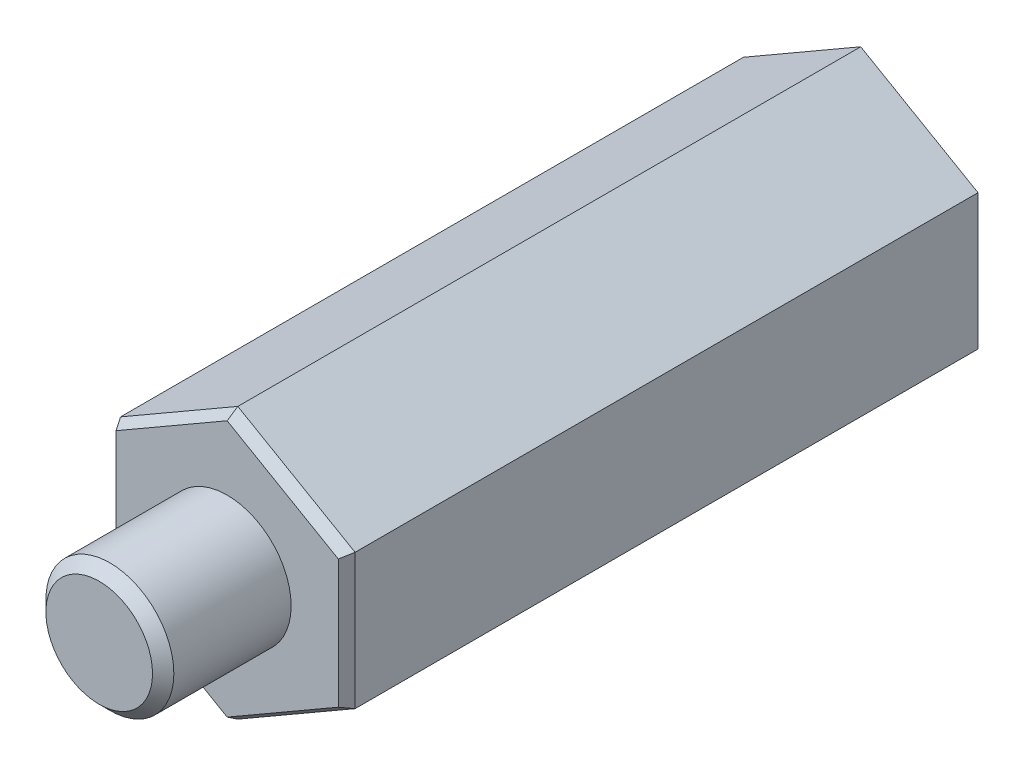
SolidWorks part; units mm, degrees
material "ｽﾃﾝﾚｽ鋼(鋳造)"
ref_plane "正面" through (0, 0, 0) normal (0, 0, 1) x (1, 0, 0)
ref_plane "平面" through (0, 0, 0) normal (0, 1, 0) x (1, 0, 0)
ref_plane "右側面" through (0, 0, 0) normal (1, 0, 0) x (0, 0, -1)
sketch "ｽｹｯﾁ1" plane through (0, 0, 0) normal (0, 0, 1) x (1, 0, 0)
  line L1 (-2.75, 1.5877) -> (-2.75, -1.5877)
  line L2 (-2.75, -1.5877) -> (0, -3.1754)
  line L3 (0, -3.1754) -> (2.75, -1.5877)
  line L4 (2.75, -1.5877) -> (2.75, 1.5877)
  line L5 (2.75, 1.5877) -> (0, 3.1754)
  line L6 (0, 3.1754) -> (-2.75, 1.5877)
  circle A0 centre (0, 0) radius 2.75 construction
  dimension "D1" = 5.5
extrude "ﾎﾞｽ - 押し出し1" add sketch "ｽｹｯﾁ1" against normal blind 15
hole_wizard "M3x0.5 ねじ穴1" positions "ｽｹｯﾁ2" profile "ｽｹｯﾁ3" tap size "M3x0.5" standard "JIS"
sketch "ｽｹｯﾁ2" plane through (0, 0, -15) normal (0, 0, -1) x (-1, 0, 0)
  point P0 (0, 0)
sketch "ｽｹｯﾁ3" plane through (0, 0, -15) normal (1, 0, 0) x (0, 1, 0)
  line L0 (0, 0) -> (0, 8.7511)
  line L1 (0, 8.7511) -> (1.25, 8)
  line L2 (1.25, 8) -> (1.25, 0.275)
  line L3 (1.25, 0.275) -> (1.525, 0)
  line L5 (1.525, 0) -> (0, 0)
  line L6 (-1.25, 0.275) -> (-1.525, 0) construction
  line L10 (0, 8.7511) -> (-1.25, 8) construction
  line L11 (0, -6.35) -> (0, 107.95) construction
  dimension "ねじ下穴ﾄﾞﾘﾙ直径" = 2.5
  dimension "ねじ下穴ﾄﾞﾘﾙの深さ" = 8
  dimension "表面の皿穴の直径" = 3.05
  dimension "表面の皿穴の角度" = 90
  dimension "ﾄﾞﾘﾙ角度" = 118
cosmetic thread "穴のねじ山1" parameters "D1"=6, "D2"=3
sketch "ｽｹｯﾁ4" plane through (0, 0, 0) normal (0, 0, 1) x (1, 0, 0)
  circle A0 centre (0, 0) radius 1.5
  dimension "D1" = 3
extrude "ﾎﾞｽ - 押し出し2" add sketch "ｽｹｯﾁ4" along normal blind 3
chamfer "面取り1" distance 0.25 angle 45 1 edges at (1.5, 0, 3)
chamfer "面取り2" distance 0.25 angle 30 12 edges at (-1.375, 2.3816, -15) (1.375, 2.3816, -15) (2.75, 0, -15) (1.375, -2.3816, -15) (-1.375, -2.3816, -15) (-2.75, 0, -15) (2.75, 0, 0) (1.375, -2.3816, 0) (-1.375, -2.3816, 0) (-2.75, 0, 0) (-1.375, 2.3816, 0) (1.375, 2.3816, 0)
